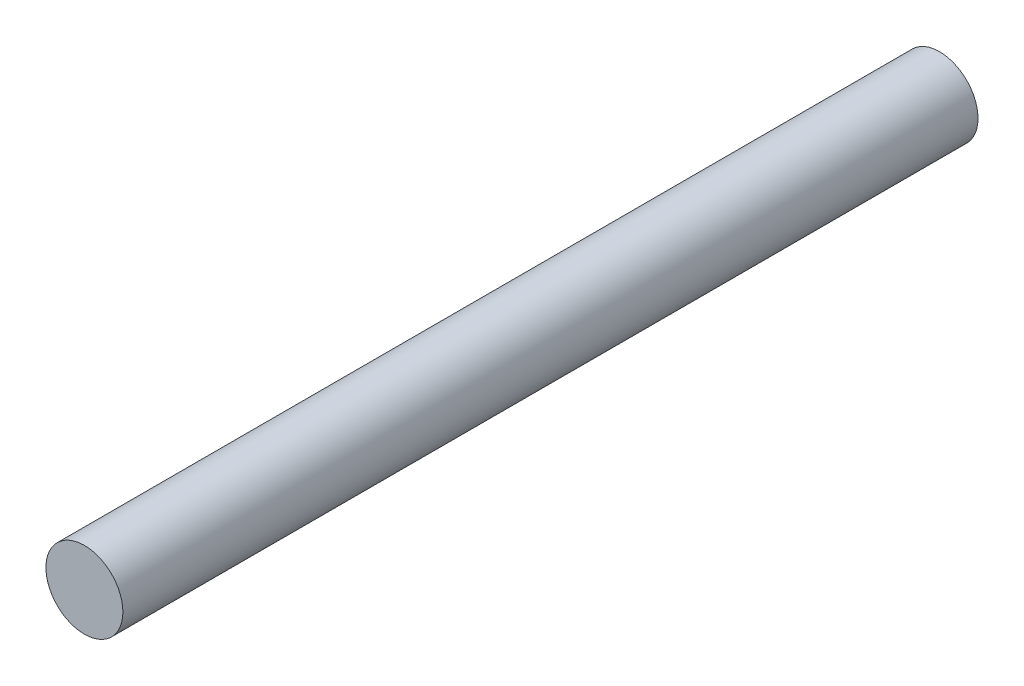
SolidWorks part; units mm, degrees
ref_plane "前视基准面" through (0, 0, 0) normal (0, 0, 1) x (1, 0, 0)
ref_plane "上视基准面" through (0, 0, 0) normal (0, 1, 0) x (1, 0, 0)
ref_plane "右视基准面" through (0, 0, 0) normal (1, 0, 0) x (0, 0, -1)
other "Configuration Table"
sketch "草图1" plane through (0, 0, 0) normal (0, 0, 1) x (1, 0, 0)
  circle A0 centre (0, 0) radius 0.9
  dimension "D1" = 1.8
extrude "凸台-拉伸1" add sketch "草图1" along normal blind 20
